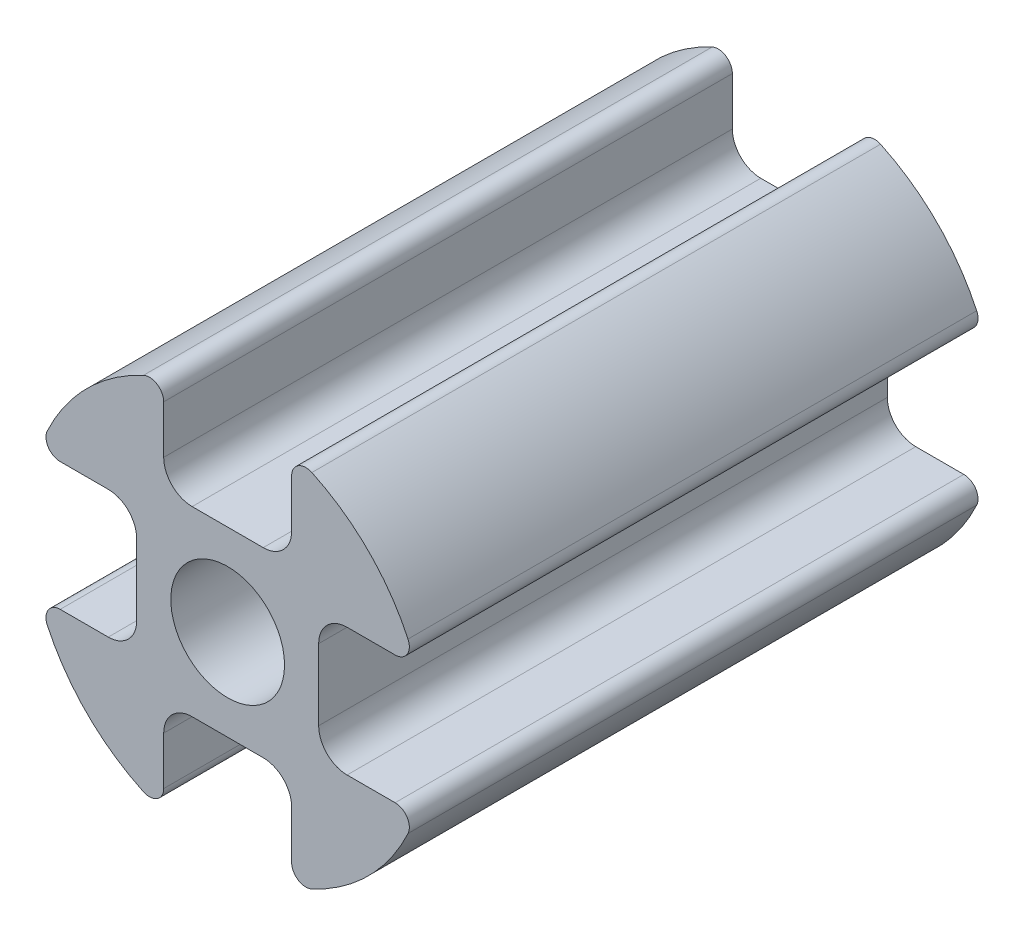
SolidWorks part; units mm, degrees
ref_plane "前视基准面" through (0, 0, 0) normal (0, 0, 1) x (1, 0, 0)
ref_plane "上视基准面" through (0, 0, 0) normal (0, 1, 0) x (1, 0, 0)
ref_plane "右视基准面" through (0, 0, 0) normal (1, 0, 0) x (0, 0, -1)
other "Configuration Table"
sketch "草图2" plane through (0, 0, 0) normal (0, 0, 1) x (1, 0, 0)
  circle A0 centre (0, 0) radius 7
  dimension "D1" = 14
extrude "凸台-拉伸1" add sketch "草图2" along normal blind 20 contours A0
sketch "草图4" plane through (0, 0, 20) normal (0, 0, 1) x (1, 0, 0)
  line L0 (0, 7) -> (0, -7) construction
  line L1 (-7, 0) -> (7, 0) construction
  line L2 (0, 7) -> (7, 7) construction
  line L3 (7, 7) -> (7, -7) construction
  line L4 (7, -7) -> (-7, -7) construction
  line L5 (-7, -7) -> (-7, 7) construction
  line L6 (-7, 7) -> (0, 7) construction
  line L8 (-2.25, 7) -> (2.25, 7)
  line L9 (-2.25, 7) -> (-2.25, 3.2)
  line L10 (-2.25, 3.2) -> (2.25, 3.2)
  line L11 (2.25, 7) -> (2.25, 3.2)
  line L12 (7, 2.25) -> (3.2, 2.25)
  line L13 (7, 2.25) -> (7, -2.25)
  line L14 (7, -2.25) -> (3.2, -2.25)
  line L15 (3.2, 2.25) -> (3.2, -2.25)
  line L16 (2.25, -7) -> (-2.25, -7)
  line L17 (2.25, -7) -> (2.25, -3.2)
  line L18 (2.25, -3.2) -> (-2.25, -3.2)
  line L19 (-2.25, -7) -> (-2.25, -3.2)
  line L20 (-7, -2.25) -> (-3.2, -2.25)
  line L21 (-7, -2.25) -> (-7, 2.25)
  line L22 (-7, 2.25) -> (-3.2, 2.25)
  line L23 (-3.2, -2.25) -> (-3.2, 2.25)
  circle A0 centre (0, 0) radius 7 construction
  dimension "D1" = 3.8
  dimension "D2" = 3.8
  dimension "D3" = 3.8
  dimension "D4" = 3.8
  dimension "D5" = 2.25
  dimension "D6" = 4.5
  dimension "D7" = 4.5
  dimension "D8" = 2.25
  dimension "D9" = 4.5
  dimension "D10" = 2.25
  dimension "D11" = 4.5
  dimension "D12" = 2.25
extrude "切除-拉伸1" cut sketch "草图4" against normal up to surface (20 mm away) up to face at (7, 0, 0)
sketch "草图5" plane through (0, 0, 20) normal (0, 0, 1) x (1, 0, 0)
  circle A0 centre (0, 0) radius 2
  dimension "D1" = 4
extrude "切除-拉伸2" cut sketch "草图5" against normal up to surface (20 mm away) up to face at (0, 0, 0)
fillet "圆角1" radius 1 8 edges at (2.25, -3.2, 10) (-2.25, -3.2, 10) (3.2, -2.25, 10) (3.2, 2.25, 10) (2.25, 3.2, 10) (-2.25, 3.2, 10) (-3.2, 2.25, 10) (-3.2, -2.25, 10)
fillet "圆角2" radius 0.5 8 edges at (2.25, 6.6285, 10) (6.6285, 2.25, 10) (6.6285, -2.25, 10) (2.25, -6.6285, 10) (-2.25, -6.6285, 10) (-6.6285, -2.25, 10) (-6.6285, 2.25, 10) (-2.25, 6.6285, 10)
